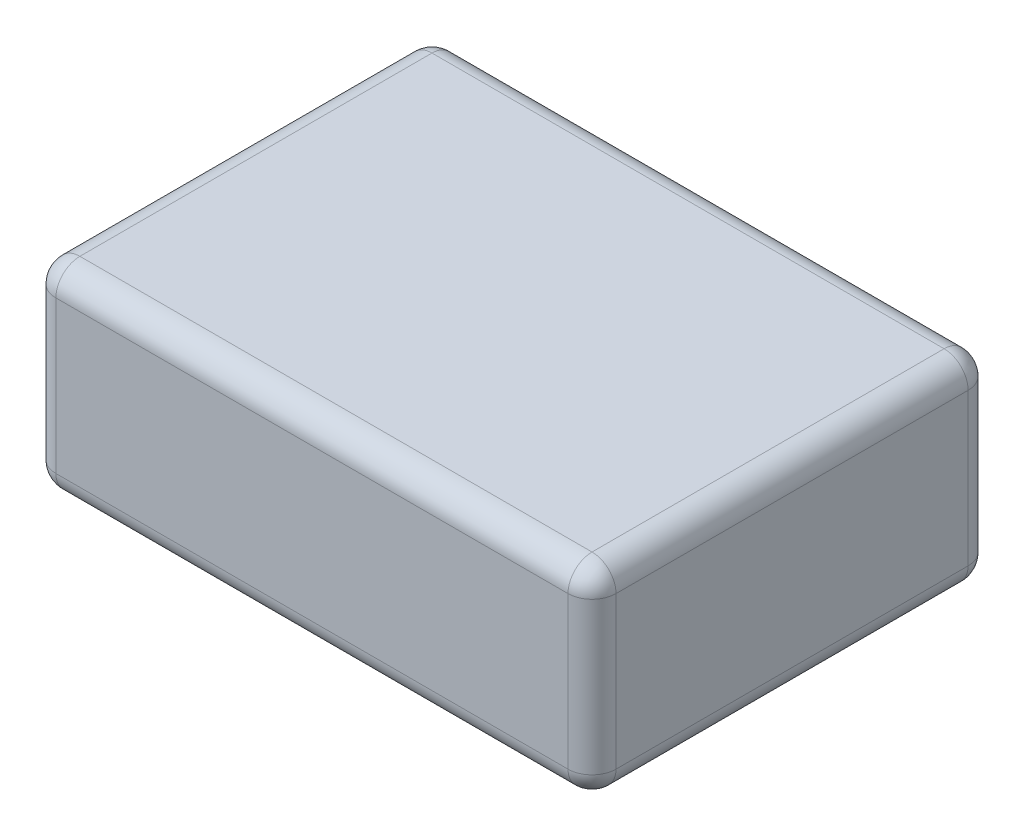
SolidWorks part; units mm, degrees
ref_plane "Front Plane" through (0, 0, 0) normal (0, 0, 1) x (1, 0, 0)
ref_plane "Top Plane" through (0, 0, 0) normal (0, 1, 0) x (1, 0, 0)
ref_plane "Right Plane" through (0, 0, 0) normal (1, 0, 0) x (0, 0, -1)
sketch "Sketch2" plane through (0, 0, 0) normal (0, 1, 0) x (1, 0, 0)
  line L1 (-88.9, 63.5) -> (88.9, 63.5)
  line L2 (-88.9, 63.5) -> (-88.9, -63.5)
  line L3 (-88.9, -63.5) -> (88.9, -63.5)
  line L4 (88.9, 63.5) -> (88.9, -63.5)
  line L5 (-88.9, 63.5) -> (88.9, -63.5) construction
  line L6 (-88.9, -63.5) -> (88.9, 63.5) construction
  point P0 (0, 0)
  dimension "D1" = 177.8
  dimension "D2" = 127
extrude "Boss-Extrude1" add sketch "Sketch2" along normal blind 63.5
fillet "Fillet1" radius 7.62 3 edges at (-88.9, 31.75, 63.5) (-88.9, 63.5, 0) (0, 63.5, 63.5)
fillet "Fillet2" radius 7.62 3 edges at (88.9, 61.2682, 61.2682) (88.9, 63.5, -3.81) (88.9, 27.94, 63.5)
fillet "Fillet3" radius 7.62 11 edges at (-86.6682, 0, 61.2682) (86.6682, 0, 61.2682) (86.6682, 61.2682, -63.5) (-86.6682, 61.2682, -63.5) (-88.9, 0, -3.81) (0, 0, 63.5) (88.9, 0, -3.81) (0, 0, -63.5) (-88.9, 27.94, -63.5) (88.9, 27.94, -63.5) (0, 63.5, -63.5)
